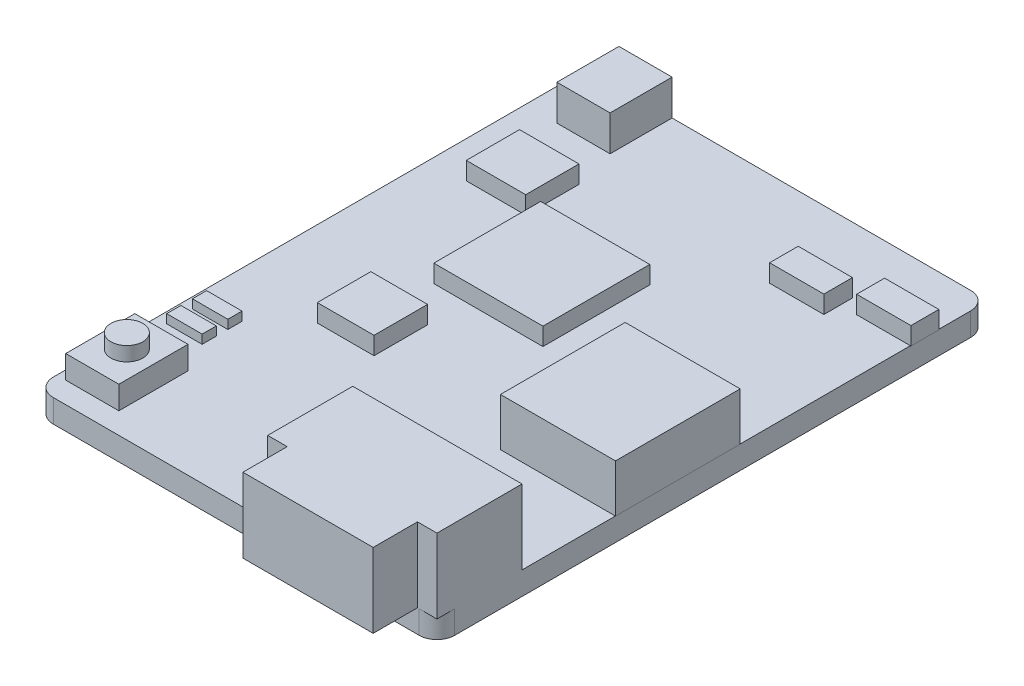
SolidWorks part; units mm, degrees
ref_plane "Front Plane" through (0, 0, 0) normal (0, 0, 1) x (1, 0, 0)
ref_plane "Top Plane" through (0, 0, 0) normal (0, 1, 0) x (1, 0, 0)
ref_plane "Right Plane" through (0, 0, 0) normal (1, 0, 0) x (0, 0, -1)
sketch "Sketch1" plane through (0, 0, 0) normal (0, 1, 0) x (1, 0, 0)
  line L1 (-11.325, -15.56) -> (11.325, -15.56)
  line L2 (-11.325, -15.56) -> (-11.325, 15.56)
  line L3 (-11.325, 15.56) -> (11.325, 15.56)
  line L4 (11.325, -15.56) -> (11.325, 15.56)
  line L5 (-11.325, -15.56) -> (11.325, 15.56) construction
  line L6 (-11.325, 15.56) -> (11.325, -15.56) construction
  point P0 (0, 0)
  dimension "D1" = 31.12
  dimension "D2" = 22.65
extrude "PCB" add sketch "Sketch1" along normal blind 1.3
sketch "Sketch2" plane through (0, 1.3, 0) normal (0, 1, 0) x (1, 0, 0)
  line L0 (-11.325, -15.56) -> (11.325, -15.56) construction
  line L1 (11.325, -10.76) -> (1.775, -10.76)
  line L2 (11.325, -10.76) -> (11.325, -18.06)
  line L3 (11.325, -18.06) -> (1.775, -18.06)
  line L4 (1.775, -10.76) -> (1.775, -18.06)
  line L5 (11.325, -15.56) -> (11.325, 15.56) construction
  dimension "D1" = 7.3
  dimension "D2" = 2.5
  dimension "D3" = 9.55
  dimension "D4" = 0
extrude "IO connector" add sketch "Sketch2" along normal blind 4.2
sketch "Sketch3" plane through (0, 1.3, 0) normal (0, 1, 0) x (1, 0, 0)
  line L0 (11.325, 15.56) -> (-11.325, 15.56) construction
  line L1 (-9.525, 15.56) -> (-6.525, 15.56)
  line L2 (-9.525, 15.56) -> (-9.525, 12.06)
  line L3 (-9.525, 12.06) -> (-6.525, 12.06)
  line L4 (-6.525, 15.56) -> (-6.525, 12.06)
  line L5 (-11.325, 15.56) -> (-11.325, -15.56) construction
  dimension "D1" = 3
  dimension "D2" = 3.5
  dimension "D3" = 1.8
extrude "Antenna connector" add sketch "Sketch3" along normal blind 2
sketch "Sketch15" plane through (0, 1.3, 0) normal (0, 1, 0) x (1, 0, 0)
  line L0 (-11.325, 15.56) -> (-11.325, -15.56) construction
  line L1 (-10.825, -14.36) -> (-7.825, -14.36)
  line L2 (-10.825, -14.36) -> (-10.825, -10.46)
  line L3 (-10.825, -10.46) -> (-7.825, -10.46)
  line L4 (-7.825, -14.36) -> (-7.825, -10.46)
  line L5 (-11.325, -15.56) -> (1.775, -15.56) construction
  dimension "D1" = 3.9
  dimension "D2" = 3
  dimension "D3" = 0.5
  dimension "D4" = 1.2
extrude "Button base" add sketch "Sketch15" along normal blind 1.3
sketch "Sketch16" plane through (0, 2.6, 0) normal (0, 1, 0) x (1, 0, 0)
  line L0 (-10.825, -12.41) -> (-7.825, -12.41) construction
  line L1 (-10.825, -10.46) -> (-10.825, -14.36) construction
  line L2 (-7.825, -14.36) -> (-7.825, -10.46) construction
  line L3 (-9.325, -10.46) -> (-9.325, -14.36) construction
  line L4 (-7.825, -10.46) -> (-10.825, -10.46) construction
  line L5 (-10.825, -14.36) -> (-7.825, -14.36) construction
  circle A0 centre (-9.325, -12.41) radius 0.9
  dimension "D1" = 1.8
extrude "Button tip" add sketch "Sketch16" along normal blind 0.8
sketch "Sketch17" plane through (0, 1.3, 0) normal (0, 1, 0) x (1, 0, 0)
  line L1 (-5.1573, 6.7739) -> (1.0006, 6.7739)
  line L2 (-5.1573, 6.7739) -> (-5.1573, 0.7442)
  line L3 (-5.1573, 0.7442) -> (1.0006, 0.7442)
  line L4 (1.0006, 6.7739) -> (1.0006, 0.7442)
  line L5 (-5.9087, 6.6822) -> (-9.2626, 6.6822)
  line L6 (-5.9087, 6.6822) -> (-5.9087, 9.6879)
  line L7 (-5.9087, 9.6879) -> (-9.2626, 9.6879)
  line L8 (-9.2626, 6.6822) -> (-9.2626, 9.6879)
  line L9 (11.3555, 12.7302) -> (8.2948, 12.7302)
  line L10 (11.3555, 12.7302) -> (11.3555, 11.1541)
  line L11 (11.3555, 11.1541) -> (8.2948, 11.1541)
  line L12 (8.2948, 12.7302) -> (8.2948, 11.1541)
  line L13 (7.3601, 11.8505) -> (4.2995, 11.8505)
  line L14 (7.3601, 11.8505) -> (7.3601, 10.2377)
  line L15 (7.3601, 10.2377) -> (4.2995, 10.2377)
  line L16 (4.2995, 11.8505) -> (4.2995, 10.2377)
  line L17 (-3.3164, -1.4486) -> (-6.5178, -1.4486)
  line L18 (-3.3164, -1.4486) -> (-3.3164, -4.4695)
  line L19 (-3.3164, -4.4695) -> (-6.5178, -4.4695)
  line L20 (-6.5178, -1.4486) -> (-6.5178, -4.4695)
extrude "Low chips" add sketch "Sketch17" along normal blind 1
sketch "Sketch18" plane through (0, 1.3, 0) normal (0, 1, 0) x (1, 0, 0)
  line L1 (11.3334, -5.4928) -> (4.8405, -5.4928)
  line L2 (11.3334, -5.4928) -> (11.3334, 1.5455)
  line L3 (11.3334, 1.5455) -> (4.8405, 1.5455)
  line L4 (4.8405, -5.4928) -> (4.8405, 1.5455)
extrude "High chips" add sketch "Sketch18" along normal blind 2.7
sketch "Sketch23" plane through (0, 1.3, 0) normal (0, 1, 0) x (1, 0, 0)
  line L0 (-11.325, -15.56) -> (1.775, -15.56) construction
  line L1 (-10.725, -7.96) -> (-8.725, -7.96)
  line L2 (-10.725, -7.96) -> (-10.725, -8.76)
  line L3 (-10.725, -8.76) -> (-8.725, -8.76)
  line L4 (-8.725, -7.96) -> (-8.725, -8.76)
  line L5 (-10.725, -7.31) -> (-8.725, -7.31)
  line L6 (-10.725, -7.31) -> (-10.725, -6.51)
  line L7 (-10.725, -6.51) -> (-8.725, -6.51)
  line L8 (-8.725, -7.31) -> (-8.725, -6.51)
  line L9 (-11.325, 15.56) -> (-11.325, -15.56) construction
  dimension "D1" = 0.8
  dimension "D2" = 2
  dimension "D3" = 6.8
  dimension "D4" = 2.25
  dimension "D5" = 0.6
extrude "LEDs" add sketch "Sketch23" along normal blind 0.5
fillet "Corners" radius 1 4 edges at (11.325, 0.65, 15.56) (-11.325, 0.65, 15.56) (-11.325, 0.65, -15.56) (11.325, 0.65, -15.56)
sketch "Sketch24" plane through (0, 5.5, 0) normal (0, 1, 0) x (1, 0, 0)
  line L0 (-10.325, -15.56) -> (1.775, -15.56) construction
  line L1 (11.325, -18.06) -> (10.225, -18.06)
  line L2 (11.325, -18.06) -> (11.325, -15.56)
  line L3 (11.325, -15.56) -> (10.225, -15.56)
  line L4 (10.225, -18.06) -> (10.225, -15.56)
  line L5 (11.325, -18.06) -> (10.225, -15.56) construction
  line L6 (11.325, -15.56) -> (10.225, -18.06) construction
  line L7 (1.775, -18.06) -> (2.875, -18.06)
  line L8 (1.775, -18.06) -> (1.775, -15.56)
  line L9 (1.775, -15.56) -> (2.875, -15.56)
  line L10 (2.875, -18.06) -> (2.875, -15.56)
  line L11 (1.775, -18.06) -> (2.875, -15.56) construction
  line L12 (1.775, -15.56) -> (2.875, -18.06) construction
  point P4 (10.775, -16.81)
  point P10 (2.325, -16.81)
  dimension "D1" = 1.1
extrude "Cut-Extrude1" cut sketch "Sketch24" against normal up to next
